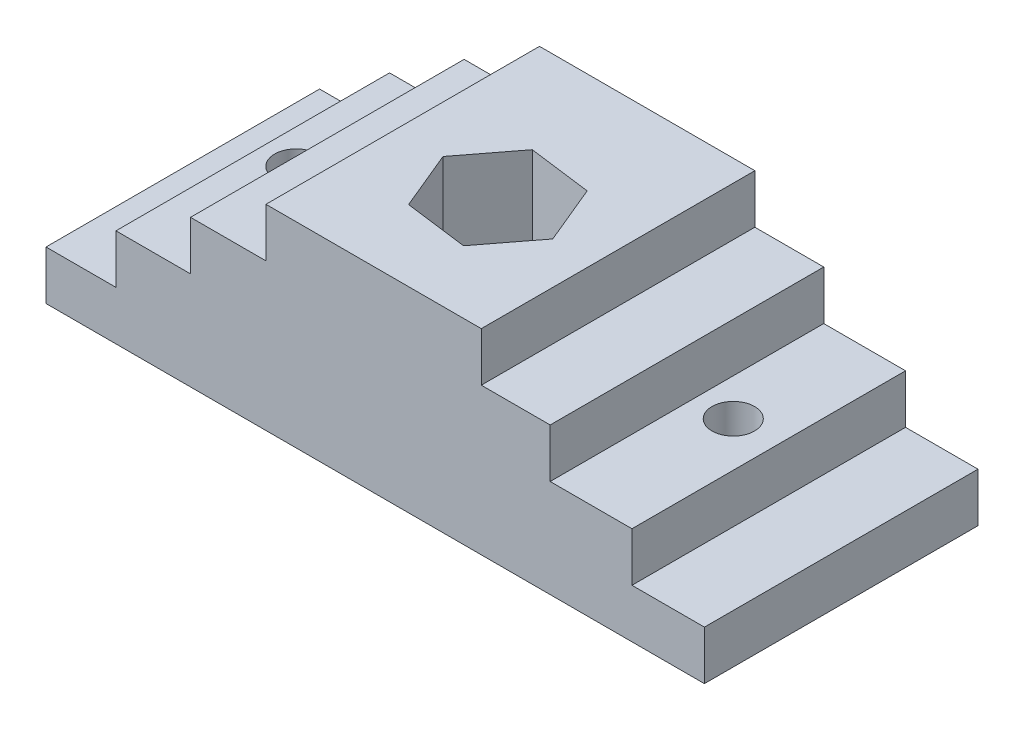
SolidWorks part; units mm, degrees
ref_plane "Front Plane" through (0, 0, 0) normal (0, 0, 1) x (1, 0, 0)
ref_plane "Top Plane" through (0, 0, 0) normal (0, 1, 0) x (1, 0, 0)
ref_plane "Right Plane" through (0, 0, 0) normal (1, 0, 0) x (0, 0, -1)
sketch "Sketch1" plane through (0, 0, 0) normal (0, 1, 0) x (1, 0, 0)
  line L1 (-121.5406, 55.0411) -> (147.322, 55.0411)
  line L2 (-121.5406, 55.0411) -> (-121.5406, -56.678)
  line L3 (-121.5406, -56.678) -> (147.322, -56.678)
  line L4 (147.322, 55.0411) -> (147.322, -56.678)
  dimension "D1" = 268.8626
extrude "Boss-Extrude1" add sketch "Sketch1" along normal blind 20
sketch "Sketch2" plane through (0, 20, 0) normal (0, 1, 0) x (1, 0, 0)
  line L0 (147.322, 55.0411) -> (-121.5406, 55.0411) construction
  line L1 (-92.977, 55.0411) -> (117.7352, 55.0411)
  line L2 (-92.977, 55.0411) -> (-92.977, -56.678)
  line L3 (-92.977, -56.678) -> (117.7352, -56.678)
  line L4 (117.7352, 55.0411) -> (117.7352, -56.678)
  line L5 (-121.5406, -56.678) -> (147.322, -56.678) construction
  dimension "D1" = 210.7122
extrude "Boss-Extrude2" add sketch "Sketch2" along normal blind 20
sketch "Sketch3" plane through (0, 40, 0) normal (0, 1, 0) x (1, 0, 0)
  line L0 (117.7352, 55.0411) -> (-92.977, 55.0411) construction
  line L1 (-62.5244, 55.0411) -> (84.3356, 55.0411)
  line L2 (-62.5244, 55.0411) -> (-62.5244, -56.678)
  line L3 (-62.5244, -56.678) -> (84.3356, -56.678)
  line L4 (84.3356, 55.0411) -> (84.3356, -56.678)
  line L5 (-92.977, -56.678) -> (117.7352, -56.678) construction
  dimension "D1" = 146.86
extrude "Boss-Extrude3" add sketch "Sketch3" along normal blind 20
sketch "Sketch5" plane through (0, 60, 0) normal (0, 1, 0) x (1, 0, 0)
  line L0 (84.3356, 55.0411) -> (-62.5244, 55.0411) construction
  line L1 (-31.7393, 55.0411) -> (56.208, 55.0411)
  line L2 (-31.7393, 55.0411) -> (-31.7393, -56.678)
  line L3 (-31.7393, -56.678) -> (56.208, -56.678)
  line L4 (56.208, 55.0411) -> (56.208, -56.678)
  line L5 (-62.5244, -56.678) -> (84.3356, -56.678) construction
  dimension "D1" = 87.9473
extrude "Boss-Extrude5" add sketch "Sketch5" along normal blind 20
sketch "Sketch9" plane through (0, 40, 0) normal (0, 1, 0) x (1, 0, 0)
  circle A0 centre (-78.9946, 2.9007) radius 8.751
  circle A1 centre (99.5254, 2.9007) radius 8.6851
extrude "Cut-Extrude3" cut sketch "Sketch9" against normal through all
sketch "Sketch10" plane through (0, 80, 0) normal (0, 1, 0) x (1, 0, 0)
  line L1 (23.2641, -31.016) -> (39.0827, -10.3775)
  line L2 (39.0827, -10.3775) -> (29.1186, 13.6411)
  line L3 (29.1186, 13.6411) -> (3.3358, 17.0211)
  line L4 (3.3358, 17.0211) -> (-12.4828, -3.6173)
  line L5 (-12.4828, -3.6173) -> (-2.5187, -27.6359)
  line L6 (-2.5187, -27.6359) -> (23.2641, -31.016)
  circle A0 centre (13.2999, -6.9974) radius 22.5196 construction
extrude "Cut-Extrude4" cut sketch "Sketch10" against normal through all
